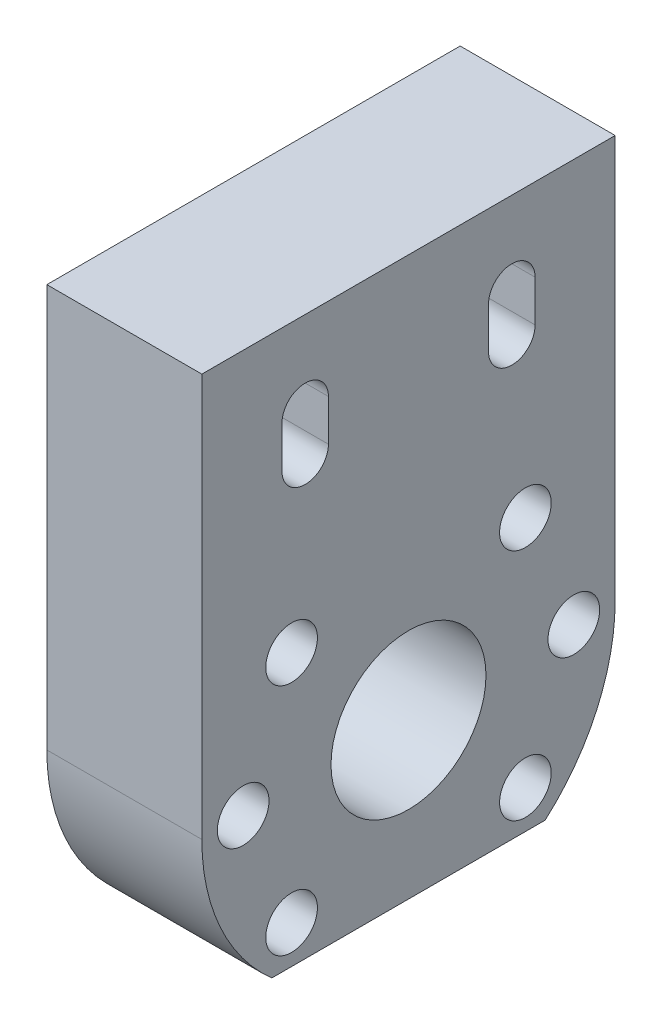
SolidWorks part; units mm, degrees
ref_plane "Front Plane" through (0, 0, 0) normal (0, 0, 1) x (1, 0, 0)
ref_plane "Top Plane" through (0, 0, 0) normal (0, 1, 0) x (1, 0, 0)
ref_plane "Right Plane" through (0, 0, 0) normal (1, 0, 0) x (0, 0, -1)
sketch "Sketch1" plane through (0, 0, 0) normal (1, 0, 0) x (0, 0, -1)
  line L0 (-13.2288, -15) -> (13.2288, -15)
  line L1 (0, 55) -> (0, -55) construction
  line L3 (-20, 0) -> (-20, 39)
  line L4 (-20, 39) -> (20, 39)
  line L5 (20, 0) -> (20, 39)
  line L7 (-12.25, 27) -> (-12.25, 31)
  line L9 (-7.75, 27) -> (-7.75, 31)
  line L10 (12.25, 27) -> (12.25, 31)
  line L11 (7.75, 27) -> (7.75, 31)
  circle A1 centre (0, 0) radius 7.5
  arc A3 (-13.2288, -15) -> (-20, 0) centre (0, 0) cw
  arc A4 (20, 0) -> (13.2288, -15) centre (0, 0) cw
  circle A6 centre (16, 0) radius 2.5
  circle A13 centre (11.3137, -11.3137) radius 2.5
  circle A15 centre (-11.3137, -11.3137) radius 2.5
  circle A16 centre (-16, 0) radius 2.5
  circle A17 centre (-11.3137, 11.3137) radius 2.5
  circle A19 centre (11.3137, 11.3137) radius 2.5
  circle A20 centre (0, 16) radius 2.5 [skipped]
  circle A21 centre (0, -16) radius 2.5 [skipped]
  arc A24 (-12.25, 31) -> (-7.75, 31) centre (-10, 31) cw
  arc A25 (-7.75, 27) -> (-12.25, 27) centre (-10, 27) cw
  arc A26 (12.25, 31) -> (7.75, 31) centre (10, 31) ccw
  arc A27 (7.75, 27) -> (12.25, 27) centre (10, 27) ccw
  point P5 (0, -15)
  point P29 (0, 0)
  dimension "D1" = 20
  dimension "D3" = 15
  dimension "D6" = 20
  dimension "D8" = 5
  dimension "D9" = 8
  dimension "D2" = 15
  dimension "D4" = 40
  dimension "D5" = 54
  dimension "D13" = 4.5
  dimension "D14" = 4
extrude "Boss-Extrude1" add sketch "Sketch1" along normal blind 15
